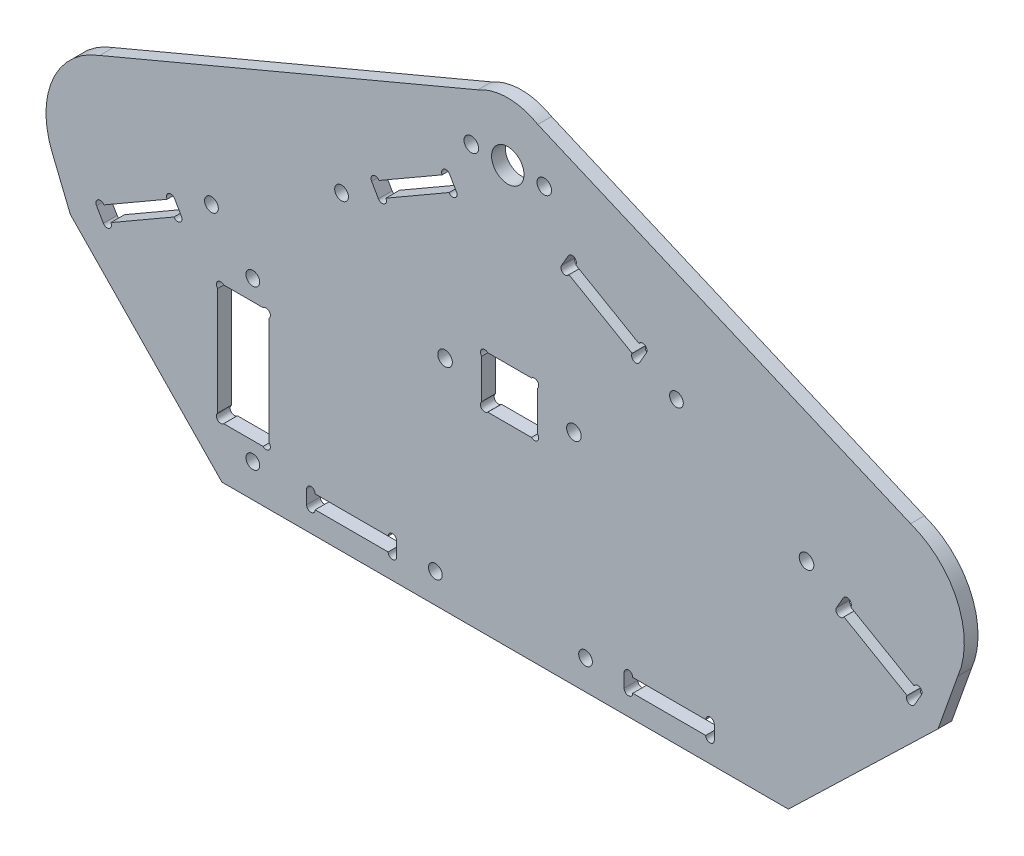
SolidWorks part; units mm, degrees
ref_plane "Front Plane" through (0, 0, 0) normal (0, 0, 1) x (1, 0, 0)
ref_plane "Top Plane" through (0, 0, 0) normal (0, 1, 0) x (1, 0, 0)
ref_plane "Right Plane" through (0, 0, 0) normal (1, 0, 0) x (0, 0, -1)
sketch "Model" plane through (0, 0, 0) normal (0, 0, 1) x (1, 0, 0)
  line L0 (99, 100) -> (99, 72)
  line L1 (99, 72) -> (87, 72)
  line L2 (87, 72) -> (87, 100)
  line L3 (87, 100) -> (99, 100)
  line L4 (88, 60) -> (220, 60)
  line L5 (88, 60) -> (52.6771, 96.363)
  line L6 (52.6771, 96.363) -> (48.5104, 106.5761)
  line L7 (220, 60) -> (254.8826, 93.6405)
  line L8 (254.8826, 93.6405) -> (259.4896, 106.5761)
  line L9 (147.6171, 168.9801) -> (59.5016, 131.8542)
  line L10 (161.6171, 168.9801) -> (248.4984, 131.8542)
  line L11 (181.7345, 65.2574) -> (181.7355, 68.4574)
  line L12 (249.3993, 95.7703) -> (231.2162, 106.2761)
  line L13 (60.3746, 98.4289) -> (58.7755, 101.2007)
  line L14 (251.0002, 98.5411) -> (232.8171, 109.0469)
  line L15 (181.7355, 68.4574) -> (202.7355, 68.4507)
  line L16 (128.7345, 65.2744) -> (128.7355, 68.4744)
  line L18 (78.5645, 108.9231) -> (76.9654, 111.6949)
  line L19 (142.6622, 145.9026) -> (124.4723, 135.4084)
  line L20 (107.7355, 68.4811) -> (128.7355, 68.4744)
  line L21 (136.0359, 145.7741) -> (122.8732, 138.1802)
  line L22 (251.0002, 98.5411) -> (249.3993, 95.7703)
  line L23 (58.7755, 101.2007) -> (76.9654, 111.6949)
  line L24 (141.0631, 148.6744) -> (142.6622, 145.9026)
  line L25 (141.0631, 148.6744) -> (136.0359, 145.7741)
  line L26 (181.7345, 65.2574) -> (202.7345, 65.2507)
  line L28 (167.1422, 143.2967) -> (168.7431, 146.0675)
  line L29 (232.8171, 109.0469) -> (231.2162, 106.2761)
  line L31 (122.8732, 138.1802) -> (124.4723, 135.4084)
  line L32 (185.3253, 132.7909) -> (186.9262, 135.5616)
  line L33 (202.7345, 65.2507) -> (202.7355, 68.4507)
  line L35 (107.7345, 65.2811) -> (107.7355, 68.4811)
  line L36 (168.7431, 146.0675) -> (186.9262, 135.5616)
  line L37 (60.3746, 98.4289) -> (78.5645, 108.9231)
  line L38 (167.1422, 143.2967) -> (185.3253, 132.7909)
  line L39 (107.7345, 65.2811) -> (128.7345, 65.2744)
  line L40 (148.5357, 105.0898) -> (148.5357, 117.0898)
  line L41 (161.5357, 117.0898) -> (161.5357, 105.0898)
  line L42 (161.5357, 105.0898) -> (148.5357, 105.0898)
  line L43 (148.5357, 117.0898) -> (161.5357, 117.0898)
  arc A2 (59.5016, 131.8542) -> (48.5104, 106.5761) centre (66, 114) ccw
  arc A3 (161.6171, 168.9801) -> (147.6171, 168.9801) centre (154.6171, 156.8557) ccw
  arc A4 (259.4896, 106.5761) -> (248.4984, 131.8542) centre (242, 114) ccw
  circle A5 centre (154.6171, 157.238) radius 3.7816
  circle A6 centre (163.1146, 157.238) radius 1.7
  circle A7 centre (146.1171, 157.238) radius 1.7
  circle A8 centre (115.8771, 132.2968) radius 1.6
  circle A10 centre (137.735, 66.8715) radius 1.6
  circle A11 centre (193.9186, 129.6737) radius 1.6
  circle A13 centre (172.735, 66.8715) radius 1.6
  circle A15 centre (170.0338, 111.0829) radius 1.7
  circle A18 centre (140, 111) radius 1.7
  circle A19 centre (95.2, 104.75) radius 1.6
  circle A20 centre (85.5606, 114.8065) radius 1.6
  circle A21 centre (224.2337, 112.1583) radius 1.7
  circle A22 centre (95.2, 67.75) radius 1.6
  dimension "D7" = 3.2
  dimension "D8" = 3.2
  dimension "D9" = 1.6
  dimension "D10" = 3.2
  dimension "D11" = 1.6
  dimension "D12" = 1.6
  dimension "D13" = 3.2
  dimension "D14" = 1.6
  dimension "D15" = 1.6
  dimension "D16" = 53
extrude "Boss-Extrude2" add sketch "Model" along normal blind 3.2
sketch "Sketch1" plane through (0, 0, 3.2) normal (0, 0, 1) x (1, 0, 0)
  line L0 (60.3746, 98.4289) -> (78.5645, 108.9231) construction
  line L1 (76.9654, 111.6949) -> (58.7755, 101.2007) construction
  line L2 (128.7355, 68.4744) -> (107.7355, 68.4811) construction
  line L3 (107.7345, 65.2811) -> (128.7345, 65.2744) construction
  line L4 (181.7345, 65.2574) -> (202.7345, 65.2507) construction
  line L5 (202.7355, 68.4507) -> (181.7355, 68.4574) construction
  line L6 (231.2162, 106.2761) -> (249.3993, 95.7703) construction
  line L7 (251.0002, 98.5411) -> (232.8171, 109.0469) construction
  line L8 (167.1422, 143.2967) -> (185.3253, 132.7909) construction
  line L9 (186.9262, 135.5616) -> (168.7431, 146.0675) construction
  line L10 (124.4723, 135.4084) -> (142.6622, 145.9026) construction
  line L11 (141.0631, 148.6744) -> (136.0359, 145.7741) construction
  line L12 (136.0359, 145.7741) -> (122.8732, 138.1802) construction
  line L13 (87, 100) -> (87.7075, 99.2925) construction
  line L14 (99, 100) -> (98.2925, 99.2925) construction
  line L15 (87, 72) -> (87.7075, 72.7075) construction
  line L16 (99, 72) -> (98.2925, 72.7075) construction
  line L17 (148.5357, 105.0898) -> (149.2431, 105.7973) construction
  line L18 (148.5357, 117.0898) -> (149.2431, 116.3824) construction
  line L19 (161.5357, 117.0898) -> (160.8282, 116.3824) construction
  line L20 (161.5357, 105.0898) -> (160.8282, 105.7973) construction
  line L21 (148.5357, 105.0898) -> (161.5357, 105.0898) construction
  line L22 (99, 100) -> (87, 100) construction
  circle A0 centre (61.2412, 98.9289) radius 1.0005
  circle A1 centre (59.6421, 101.7007) radius 1.0005
  circle A2 centre (76.0988, 111.1949) radius 1.0005
  circle A3 centre (77.6979, 108.4232) radius 1.0005
  circle A4 centre (87.7075, 99.2925) radius 1.0005
  circle A5 centre (98.2925, 99.2925) radius 1.0005
  circle A6 centre (87.7075, 72.7075) radius 1.0005
  circle A7 centre (98.2925, 72.7075) radius 1.0005
  circle A8 centre (108.736, 68.4808) radius 1.0005
  circle A9 centre (108.735, 65.2808) radius 1.0005
  circle A10 centre (127.734, 65.2747) radius 1.0005
  circle A11 centre (127.735, 68.4747) radius 1.0005
  circle A12 centre (182.735, 65.2571) radius 1.0005
  circle A13 centre (182.736, 68.4571) radius 1.0005
  circle A14 centre (201.735, 68.451) radius 1.0005
  circle A15 centre (201.734, 65.251) radius 1.0005
  circle A16 centre (232.0825, 105.7756) radius 1.0005
  circle A17 centre (233.6834, 108.5464) radius 1.0005
  circle A18 centre (250.1339, 99.0416) radius 1.0005
  circle A19 centre (248.5331, 96.2708) radius 1.0005
  circle A20 centre (160.8282, 105.7973) radius 1.0005
  circle A21 centre (160.8282, 116.3824) radius 1.0005
  circle A22 centre (149.2431, 105.7973) radius 1.0005
  circle A23 centre (149.2431, 116.3824) radius 1.0005
  circle A24 centre (168.0085, 142.7962) radius 1.0005
  circle A25 centre (169.6094, 145.5669) radius 1.0005
  circle A26 centre (184.459, 133.2914) radius 1.0005
  circle A27 centre (186.0599, 136.0622) radius 1.0005
  circle A28 centre (141.7956, 145.4026) radius 1.0005
  circle A29 centre (140.1965, 148.1744) radius 1.0005
  circle A30 centre (123.7399, 138.6802) radius 1.0005
  circle A31 centre (125.339, 135.9084) radius 1.0005
  dimension "D2" = 2.001
  dimension "D1" = 45
  dimension "D3" = 45
extrude "Cut-Extrude1" cut sketch "Sketch1" against normal through all
equation "\"dim-top\"= 2.001"
equation "\"D2@Sketch1\"=\"dim-top\""
